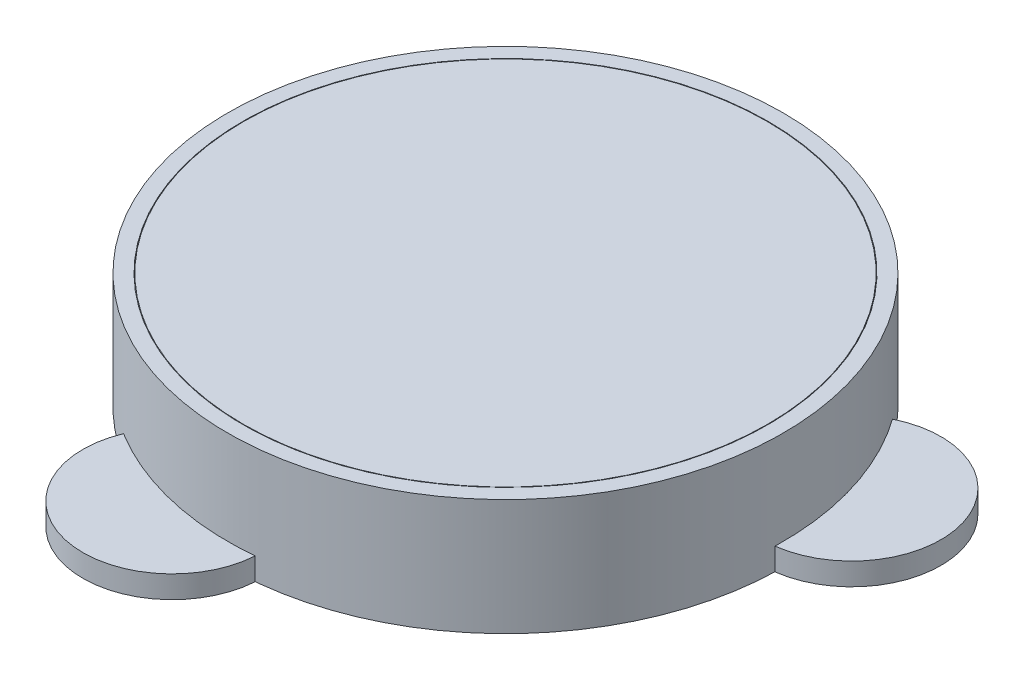
SolidWorks part; units mm, degrees
ref_plane "Спереди" through (0, 0, 0) normal (0, 0, 1) x (1, 0, 0)
ref_plane "Сверху" through (0, 0, 0) normal (0, 1, 0) x (1, 0, 0)
ref_plane "Справа" through (0, 0, 0) normal (1, 0, 0) x (0, 0, -1)
sketch "Sketch1" plane through (0, 0, 0) normal (0, 1, 0) x (1, 0, 0)
  circle A0 centre (0, 0) radius 17.5
  dimension "D1" = 35
extrude "Boss-Extrude1" add sketch "Sketch1" along normal blind 2
sketch "Sketch2" plane through (0, 2, 0) normal (0, 1, 0) x (1, 0, 0)
  circle A0 centre (0, 0) radius 17.5
extrude "Boss-Extrude2" add sketch "Sketch2" along normal blind 0.1
sketch "Sketch3" plane through (0, 2.1, 0) normal (0, 1, 0) x (1, 0, 0)
  circle A0 centre (0, 0) radius 17.4
extrude "Boss-Extrude3" add sketch "Sketch3" along normal blind 2.5
sketch "Sketch4" plane through (0, 4.6, 0) normal (0, 1, 0) x (1, 0, 0)
  circle A0 centre (0, 0) radius 17.5
extrude "Boss-Extrude4" add sketch "Sketch4" along normal blind 1.2
sketch "Sketch5" plane through (0, 5.8, 0) normal (0, 1, 0) x (1, 0, 0)
  circle A0 centre (0, 0) radius 17.6
extrude "Boss-Extrude5" add sketch "Sketch5" along normal blind 2
sketch "Sketch6" plane through (0, 0, 0) normal (0, -1, 0) x (1, 0, 0)
  circle A0 centre (0, 0) radius 17.6387
  circle A1 centre (0, 0) radius 18.6387
  circle A2 centre (0, 0) radius 17.6387
  circle M1 centre (0, 0) radius 17.5
  dimension "D1" = 1
extrude "Boss-Extrude7" add sketch "Sketch6" against normal up to surface (7.8 mm away) separate body contours A1 M1
sketch "Sketch7" plane through (0, 0, 0) normal (0, -1, 0) x (-1, 0, 0)
  circle A0 centre (13.6032, 12.7419) radius 6
  circle A1 centre (0, 0) radius 18.6387 construction
  circle A2 centre (0, 0) radius 18.6387
  circle A3 centre (0, 0) radius 18.6387
  circle A4 centre (4.2332, -18.1517) radius 6
  circle A5 centre (0, 0) radius 18.6387
  circle A6 centre (-17.8364, 5.4098) radius 6
  circle A7 centre (0, 0) radius 18.6387 construction
  point P17 (0, 0)
  circle M8 centre (0, 0) radius 18.6387
  dimension "D1" = 3
extrude "Boss-Extrude8" add sketch "Sketch7" against normal blind 1.5 separate body contours A5 A0 A3 | A5 A4 M8 | A3 A6 A2
sketch "Sketch9" plane through (0, 7.8, 0) normal (0, 1, 0) x (1, 0, 0)
  line L0 (0, 0) -> (-18.6387, 0)
  line L1 (0, 0) -> (-15.0791, 10.9556)
  line L2 (0, 0) -> (-5.7597, 17.7265)
  line L3 (0, 0) -> (5.7597, 17.7265)
  line L4 (0, 0) -> (15.0791, 10.9556)
  line L5 (0, 0) -> (18.6387, 0)
  line L6 (0, 0) -> (15.0791, -10.9556)
  line L7 (0, 0) -> (5.7597, -17.7265)
  line L8 (0, 0) -> (-5.7597, -17.7265)
  line L9 (0, 0) -> (-15.0791, -10.9556)
  circle A0 centre (0, 0) radius 17.61
  circle A1 centre (0, 0) radius 18.6387 construction
  point P19 (0, 0)
  dimension "D1" = 10
extrude "Boss-Extrude9" add sketch "Sketch9" against normal blind 1.5 from offset 2 separate body contours L7 A0 L6 | L5 A0 L4 | L3 A0 L2 | L1 A0 L0 | L9 A0 L8
